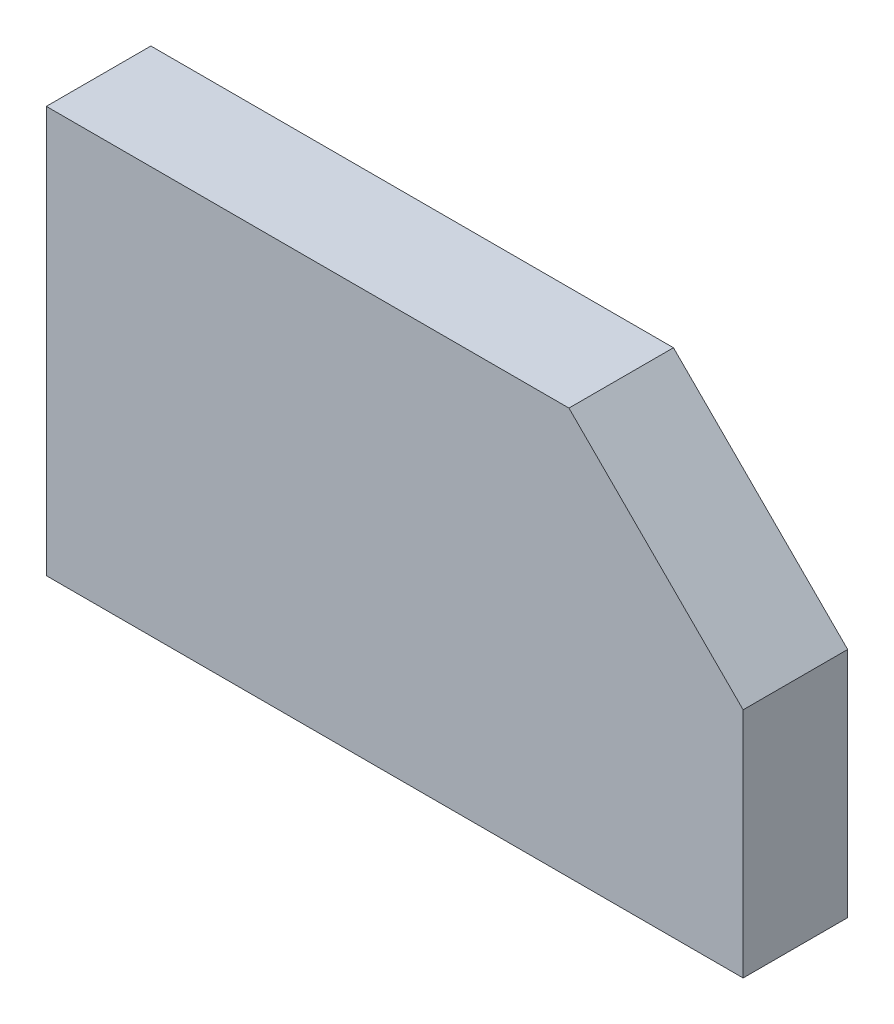
SolidWorks part; units mm, degrees
ref_plane "Front Plane" through (0, 0, 0) normal (0, 0, 1) x (1, 0, 0)
ref_plane "Top Plane" through (0, 0, 0) normal (0, 1, 0) x (1, 0, 0)
ref_plane "Right Plane" through (0, 0, 0) normal (1, 0, 0) x (0, 0, -1)
sketch "Sketch1" plane through (0, 0, 0) normal (0, 0, 1) x (1, 0, 0)
  line L0 (30, 35) -> (60, 5)
  line L1 (-60, 35) -> (30, 35)
  line L2 (-60, 35) -> (-60, -35)
  line L3 (-60, -35) -> (60, -35)
  line L4 (60, 5) -> (60, -35)
  line L5 (-60, 35) -> (60, -35) construction
  line L6 (-60, -35) -> (60, 35) construction
  point P0 (0, 0)
  dimension "D1" = 120
  dimension "D2" = 70
extrude "Boss-Extrude1" add sketch "Sketch1" along normal blind 18
hole_wizard "Ø4.0 (4) Diameter Hole1" positions "Sketch3" profile "Sketch2" hole size "Ø4.0" standard "ISO"
sketch "Sketch3" plane through (-60, 0, 0) normal (-1, 0, 0) x (0, 0, 1)
  line L0 (18, 35) -> (18, -35) construction
  line L1 (18, 35) -> (0, 35) construction
  point P0 (9, 16)
  point P2 (9, -16)
  dimension "D1" = 9
  dimension "D2" = 9
  dimension "D3" = 32
  dimension "D4" = 19
sketch "Sketch2" plane through (-60, 16, 9) normal (0, 1, 0) x (0, 0, 1)
  line L0 (0, 0) -> (0, 31.2017)
  line L1 (0, 31.2017) -> (2, 30)
  line L2 (2, 30) -> (2, 0)
  line L5 (2, 0) -> (0, 0)
  line L10 (0, 31.2017) -> (-2, 30) construction
  line L11 (0, -6.35) -> (0, 107.95) construction
  dimension "Hole Dia." = 4
  dimension "Hole Depth" = 30
  dimension "Drill Angle" = 118
hole_wizard "Ø4.0 (4) Diameter Hole2" positions "Sketch5" profile "Sketch4" hole size "Ø4.0" standard "ISO"
sketch "Sketch5" plane through (0, -35, 0) normal (0, -1, 0) x (-1, 0, 0)
  point P0 (-35, -9)
  point P3 (20, -9)
sketch "Sketch4" plane through (35, -35, 9) normal (1, 0, 0) x (0, 0, -1)
  line L0 (0, 0) -> (0, 31.2017)
  line L1 (0, 31.2017) -> (2, 30)
  line L2 (2, 30) -> (2, 0)
  line L5 (2, 0) -> (0, 0)
  line L10 (0, 31.2017) -> (-2, 30) construction
  line L11 (0, -6.35) -> (0, 107.95) construction
  dimension "Hole Dia." = 4
  dimension "Hole Depth" = 30
  dimension "Drill Angle" = 118
